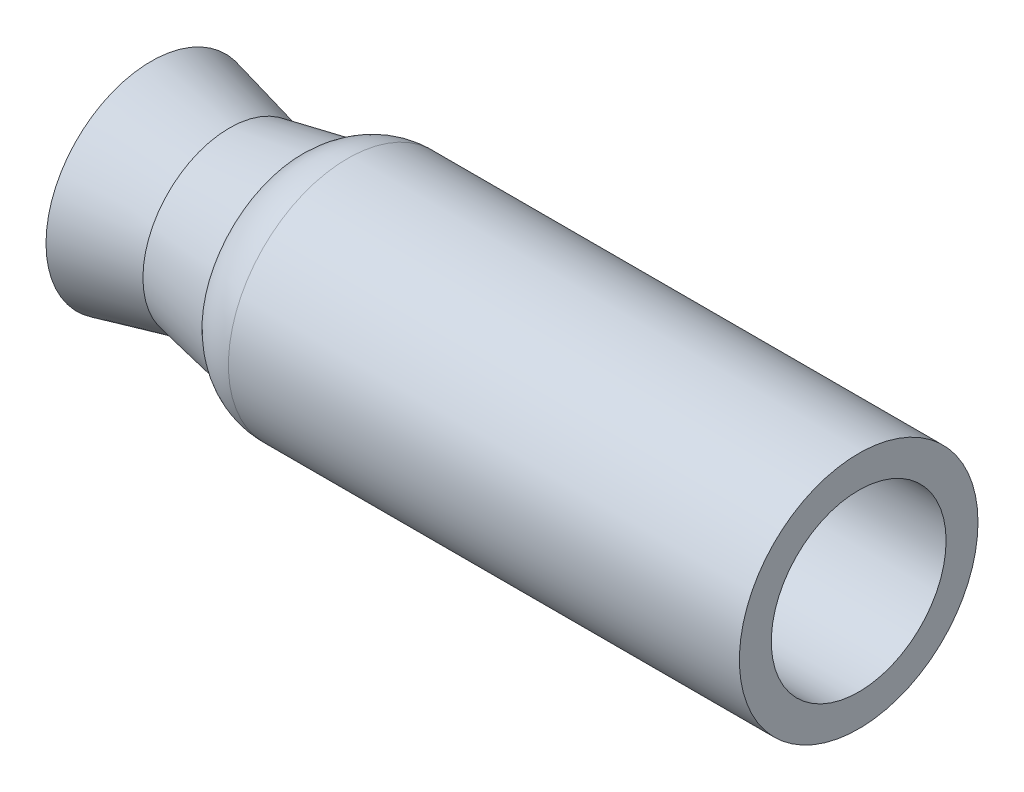
SolidWorks part; units mm, degrees
material "Thornel VCB-20 Carbon Cloth"
ref_plane "Front Plane" through (0, 0, 0) normal (0, 0, 1) x (1, 0, 0)
ref_plane "Top Plane" through (0, 0, 0) normal (0, 1, 0) x (1, 0, 0)
ref_plane "Right Plane" through (0, 0, 0) normal (1, 0, 0) x (0, 0, -1)
sketch "Sketch1" plane through (0, 0, 0) normal (0, 0, 1) x (1, 0, 0)
  line L0 (52.3226, 27.4009) -> (-107.8623, 27.4009)
  line L3 (0, 0) -> (-172.8085, 0) construction
  line L5 (-144.9334, 14.7) -> (-144.9334, 18.7) construction
  line L6 (-144.9334, 18.7) -> (-143.6334, 18.9501) construction
  line L7 (-169.4742, 32.9763) -> (-171.9334, 23.2835)
  line L8 (-122.0045, 31.5431) -> (-144.9334, 27.1315)
  line L10 (-107.8623, 37.4009) -> (52.3226, 37.4009)
  line L11 (52.3226, 37.4009) -> (52.3226, 27.4009)
  line L12 (-144.9334, 27.1315) -> (-169.4742, 32.9763)
  line L13 (-171.9334, 23.2835) -> (-187.0087, 27.1083) construction
  line L14 (-143.6334, 18.9501) -> (-143.6334, 14.2101)
  line L15 (-144.9334, 14.7) -> (-143.6334, 14.2101)
  line L16 (-143.6334, 18.9501) -> (-114.9334, 24.472)
  arc A0 (-107.8623, 27.4009) -> (-114.9334, 24.472) centre (-107.8623, 17.4009) ccw
  arc A5 (-107.8623, 37.4009) -> (-122.0045, 31.5431) centre (-107.8623, 17.4009) ccw
  parabola Q0 (-171.9334, 23.2835) -> (-144.9334, 14.7) focus (-225.4799, -74.885) apex (-225.7319, 30.0457)
  dimension "D1" = 10
  dimension "D7" = 30.0457
  dimension "D14" = 27.4009
  dimension "D16" = 167.256
  dimension "D3" = 37.4009
  dimension "D6" = 4
  dimension "D20" = 30
  dimension "D4" = 24.472
  dimension "D5" = 10
  dimension "D8" = 27
  dimension "D9" = 14.7
  dimension "D10" = 52.3226
  dimension "D11" = 23.2835
  dimension "D12" = 25.2272
  dimension "D13" = 4.74
  dimension "D15" = 28.7
  dimension "D19" = 10
revolve "Revolve1" add sketch "Sketch1" angle 360 about L3
equation "\"theta_t\"= 36.9009 - ( 426.271 / ( \"Aet\" + 7.00037 ) ) + ( 10026.8 / ( \"Aet\" + 7.00037 ) ^ 2 ) - ( 175410 / ( \"Aet\" + 7.00037 ) ^ 3 ) + ( ( 1.6742 * ( 10 ^ 6 ) ) / ( \"Aet\" + 7.00037 ) ^ 4 ) - ( ( 6.7643 * ( 10 ^ 6 ) ) / ( \"Aet\" + 7.00037 ) ^ 5 )"
equation "\"rt\"= ( 0.022412299 / 2 ) * 1000"
equation "\"re\"= sqr ( \"rt\" ^ 2 * \"Aet\" )"
equation "\"Aet\"= 4.317"
equation "\"L\"= 0.8 * ( ( \"re\" / tan ( 15 ) ) - ( \"rt\" / tan ( 15 ) ) )"
equation "\"lc\"= ( \"l*\" / \"cr\" )"
equation "\"b\"= tan ( \"theta_t\" )"
equation "\"a\"= ( \"re\" - \"b\" * \"L\" - \"c\" ) / \"L\" ^ 2"
equation "\"c\"= \"rt\" * ( 1.382 - 0.382 * cos ( \"theta_t\" ) )"
equation "\"cr\"= 5.978857531"
equation "\"rc\"= sqr ( \"cr\" * ( \"rt\" ^ 2 ) )"
equation "\"l*\"= 1000"
equation "\"th\"= 10"
equation "\"D19@Sketch1\"=\"th\""
equation "\"theta_cr\"= 45deg"
equation "\"D11@Sketch1\"=\"re\""
